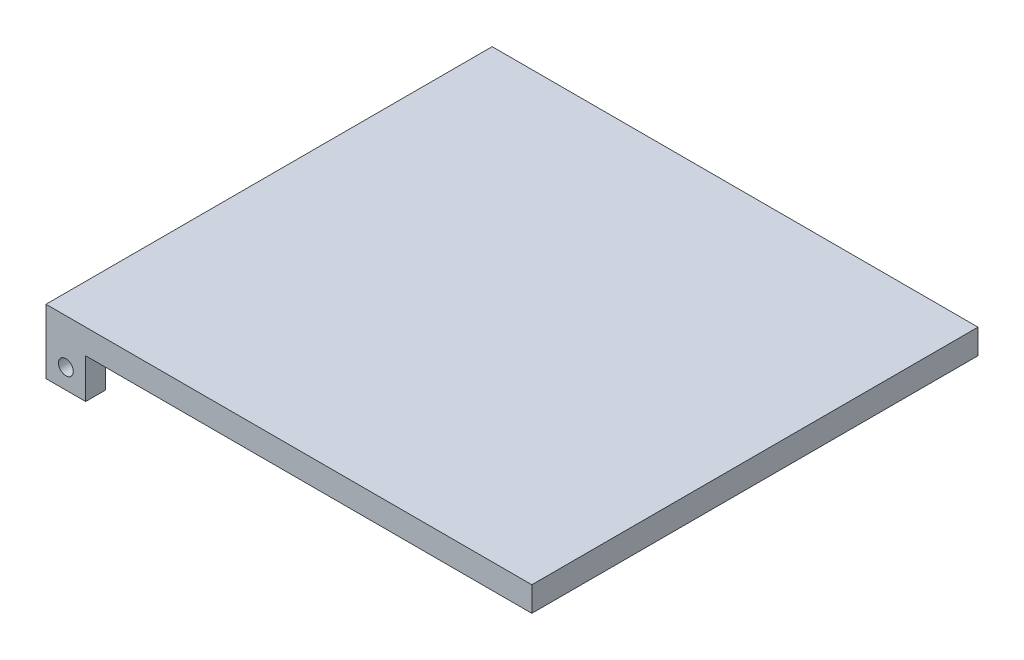
SolidWorks part; units mm, degrees
ref_plane "Спереди" through (0, 0, 0) normal (0, 0, 1) x (1, 0, 0)
ref_plane "Сверху" through (0, 0, 0) normal (0, 1, 0) x (1, 0, 0)
ref_plane "Справа" through (0, 0, 0) normal (1, 0, 0) x (0, 0, -1)
sketch "Эскиз1" plane through (0, 0, 0) normal (0, 1, 0) x (1, 0, 0)
  line L1 (-19.6, -18) -> (19.6, -18)
  line L2 (-19.6, -18) -> (-19.6, 18)
  line L3 (-19.6, 18) -> (19.6, 18)
  line L4 (19.6, -18) -> (19.6, 18)
  line L5 (-19.6, -18) -> (19.6, 18) construction
  line L6 (-19.6, 18) -> (19.6, -18) construction
  point P0 (0, 0)
  dimension "D1" = 36
  dimension "D2" = 39.2
extrude "Бобышка-Вытянуть1" add sketch "Эскиз1" along normal blind 2
sketch "Эскиз7" plane through (0, 0, 0) normal (0, -1, 0) x (1, 0, 0)
  line L0 (-19.6, -18) -> (-19.6, 18) construction
  line L1 (-19.6, -18) -> (-16.4, -18)
  line L2 (-19.6, -18) -> (-19.6, -16.4)
  line L3 (-19.6, -16.4) -> (-16.4, -16.4)
  line L4 (-16.4, -18) -> (-16.4, -16.4)
  line L5 (-19.6, 16.4) -> (-16.4, 16.4)
  line L6 (-19.6, 16.4) -> (-19.6, 18)
  line L7 (-19.6, 18) -> (-16.4, 18)
  line L8 (-16.4, 16.4) -> (-16.4, 18)
  line L9 (-19.6, 18) -> (19.6, 18) construction
  dimension "D1" = 1.6
  dimension "D2" = 3.2
  dimension "D3" = 1.6
  dimension "D4" = 3.2
extrude "Бобышка-Вытянуть3" add sketch "Эскиз7" along normal blind 3.2
sketch "Эскиз8" plane through (0, 0, -18) normal (0, 0, -1) x (-1, 0, 0)
  line L0 (19.6, 2) -> (19.6, -3.2) construction
  line L2 (19.6, -3.2) -> (16.4, -3.2) construction
  circle A0 centre (18, -1.6) radius 0.6
  point P2 (18.2102, -0.6415)
  point P3 (16.4, -1.6)
  point P4 (0, 0)
  point P5 (18.81, -0.6415)
  point P6 (16.4, -1.6)
  point P7 (18, -1.6)
  point P8 (17.9611, -1.5704)
  point P9 (16.6462, -0.7775)
  point P10 (16.4, -1.6)
  point P11 (16.4, -1.6)
  point P12 (0, 0)
  point P15 (16.4, -1.6)
  point P16 (0, 0)
  point P18 (18.1093, -3.2)
  dimension "D1" = 1.2
  dimension "D2" = 1.6
  dimension "D3" = 1.6
extrude "Вырез-Вытянуть2" cut sketch "Эскиз8" against normal up to surface (36 mm away)
